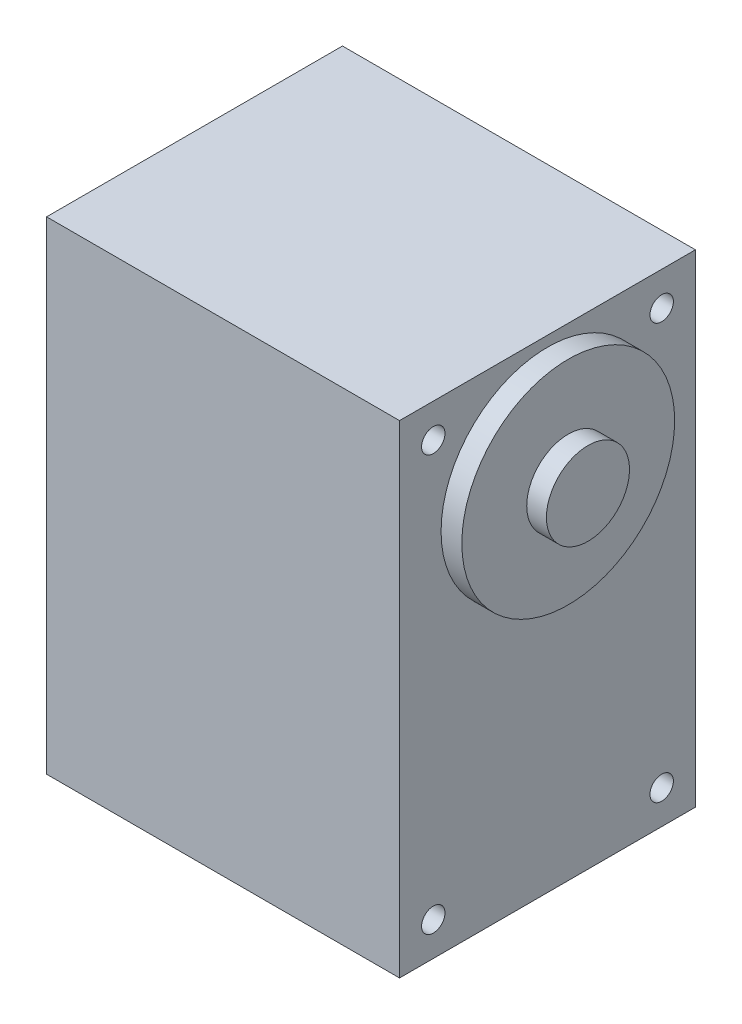
SolidWorks part; units mm, degrees
ref_plane "Front Plane" through (0, 0, 0) normal (0, 0, 1) x (1, 0, 0)
ref_plane "Top Plane" through (0, 0, 0) normal (0, 1, 0) x (1, 0, 0)
ref_plane "Right Plane" through (0, 0, 0) normal (1, 0, 0) x (0, 0, -1)
sketch "Sketch1" plane through (0, 0, 0) normal (0, 0, 1) x (1, 0, 0)
  line L1 (-17, -23.25) -> (17, -23.25)
  line L2 (-17, -23.25) -> (-17, 23.25)
  line L3 (-17, 23.25) -> (17, 23.25)
  line L4 (17, -23.25) -> (17, 23.25)
  line L5 (-17, -23.25) -> (17, 23.25) construction
  line L6 (-17, 23.25) -> (17, -23.25) construction
  point P0 (0, 0)
  dimension "D1" = 46.5
  dimension "D2" = 34
extrude "Boss-Extrude1" add sketch "Sketch1" along normal blind 28.5
sketch "Sketch2" plane through (17, 0, 0) normal (1, 0, 0) x (0, 0, -1)
  line L0 (-28.5, 23.25) -> (0, 23.25) construction
  circle A0 centre (-14.25, 12) radius 10.25
  dimension "D1" = 20.5
  dimension "D2" = 11.25
extrude "Boss-Extrude2" add sketch "Sketch2" along normal blind 2 contours A0
sketch "Sketch3" plane through (19, 0, 0) normal (1, 0, 0) x (0, 0, -1)
  circle A1 centre (-14.25, 12) radius 4
  dimension "D1" = 8
extrude "Boss-Extrude3" add sketch "Sketch3" along normal blind 1.9
sketch "Sketch10" plane through (17, 0, 0) normal (1, 0, 0) x (0, 0, -1)
  line L0 (0, -23.25) -> (0, 23.25) construction
  circle A0 centre (-3.25, 20) radius 1.1269
  circle A2 centre (-25.25, 20) radius 1.1269
  circle A5 centre (-25.25, -20) radius 1.1269
  circle A6 centre (-3.25, -20) radius 1.1269
  dimension "D4" = 3.25
  dimension "D3" = 2
extrude "Cut-Extrude2" cut sketch "Sketch10" against normal blind 4
mirror "Mirror1" about plane through (0, 0, 0) normal (1, 0, 0) of "Cut-Extrude2"
ref_plane "Plane1" through (0, 0, 14.25) normal (0, 0, -1) x (-1, 0, 0)
